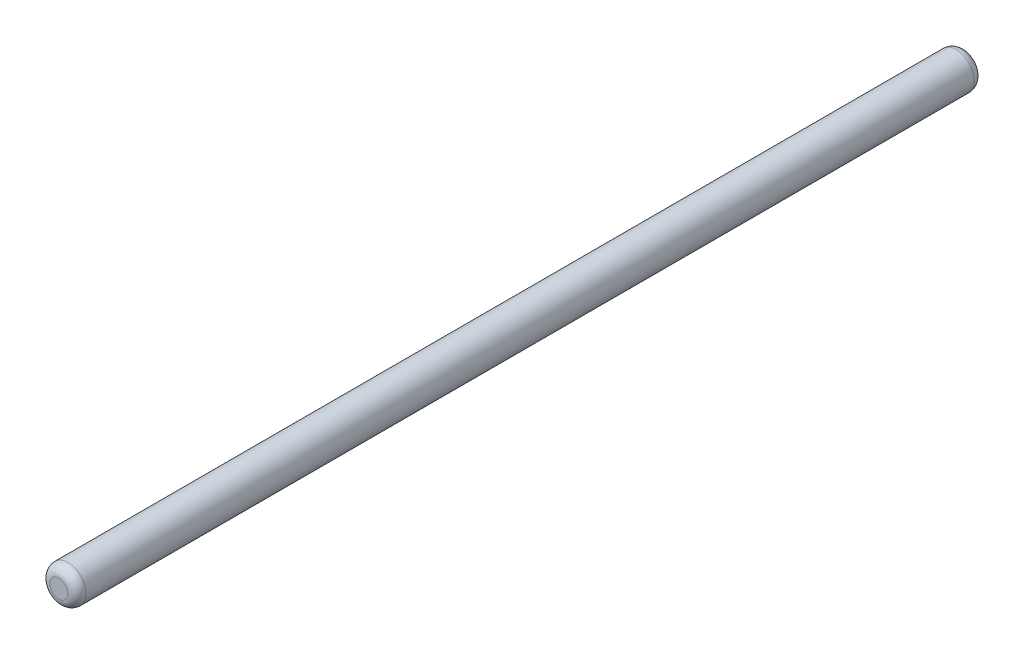
SolidWorks part; units mm, degrees
ref_plane "Front Plane" through (0, 0, 0) normal (0, 0, 1) x (1, 0, 0)
ref_plane "Top Plane" through (0, 0, 0) normal (0, 1, 0) x (1, 0, 0)
ref_plane "Right Plane" through (0, 0, 0) normal (1, 0, 0) x (0, 0, -1)
sketch "Sketch1" plane through (0, 0, 0) normal (0, 0, 1) x (1, 0, 0)
  circle A0 centre (0, 0) radius 10
  dimension "D1" = 20
extrude "Boss-Extrude1" add sketch "Sketch1" along normal blind 500
fillet "Fillet4" radius 5 1 edges at (10, 0, 500)
fillet "Fillet5" radius 5 1 edges at (10, 0, 0)
